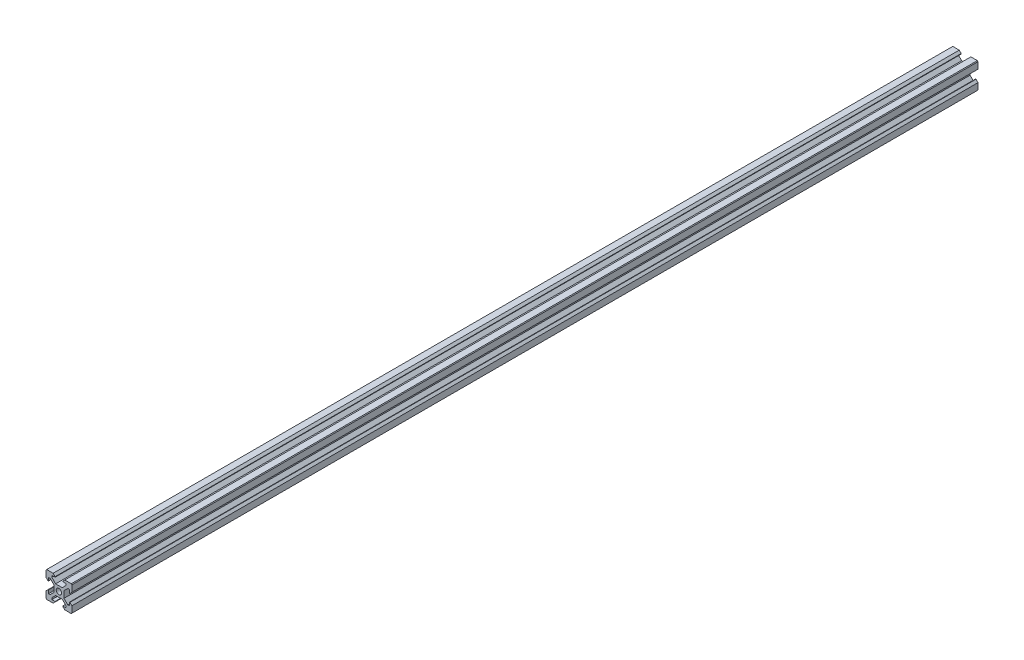
SolidWorks part; units mm, degrees
ref_plane "Front Plane" through (0, 0, 0) normal (0, 0, 1) x (1, 0, 0)
ref_plane "Top Plane" through (0, 0, 0) normal (0, 1, 0) x (1, 0, 0)
ref_plane "Right Plane" through (0, 0, 0) normal (1, 0, 0) x (0, 0, -1)
sketch "Sketch1" plane through (0, 0, 0) normal (0, 0, 1) x (1, 0, 0)
  line L0 (15.6876, 55.3211) -> (115.0437, 55.3211) construction
  line L1 (5.5, 6.8294) -> (2.5706, 3.9)
  line L2 (0, 3.9) -> (0, 2.1)
  line L3 (10, 10) -> (1.4849, 1.4849)
  line L4 (10, 10) -> (4.5, 10)
  line L5 (1.4849, 1.4849) -> (3.9, 3.9) construction
  line L6 (10, -10) -> (-10, 10) construction
  line L7 (10, 10) -> (1.4849, 1.4849) construction
  line L8 (0, 0) -> (-10, -10) construction
  line L10 (0, 3.9) -> (2.5706, 3.9)
  line L12 (-3.9, -3.9) -> (0, 0) construction
  line L13 (-3.9, 3.9) -> (3.9, -3.9) construction
  line L14 (5.5, 6.8294) -> (5.5, 8.12)
  line L15 (5.5, 8.12) -> (2.62, 8.12)
  line L16 (2.62, 8.12) -> (4.5, 10)
  line L17 (0, 2.1) -> (0, 16.7618) construction
  arc A0 (1.4849, 1.4849) -> (0, 2.1) centre (0, 0) ccw
  point P2 (0, 0)
  point P7 (0, 0)
  dimension "D3" = 45
  dimension "D4" = 6.1
  dimension "D8" = 4.2
  dimension "D1" = 20
  dimension "D2" = 11
  dimension "D5" = 1.88
  dimension "D6" = 9
  dimension "D7" = 0.94
  dimension "D9" = 3.9
extrude "Boss-Extrude1" add sketch "Sketch1" along normal blind 700
chamfer "Chamfer2" distance 0.5 angle 45 1 edges at (2.62, 8.12, 350)
mirror "Mirror1" about plane through (10, 10, 700) normal (-0.7071, 0.7071, 0) of bodies 102
chamfer "Chamfer1" distance 0.5 angle 45 1 edges at (10, 10, 350)
mirror "Mirror4" about plane through (0, 3.9, 700) normal (1, 0, 0) of bodies 103 104
mirror "Mirror5" about plane through (-3.9, 0, 700) normal (0, 1, 0) of bodies 105
